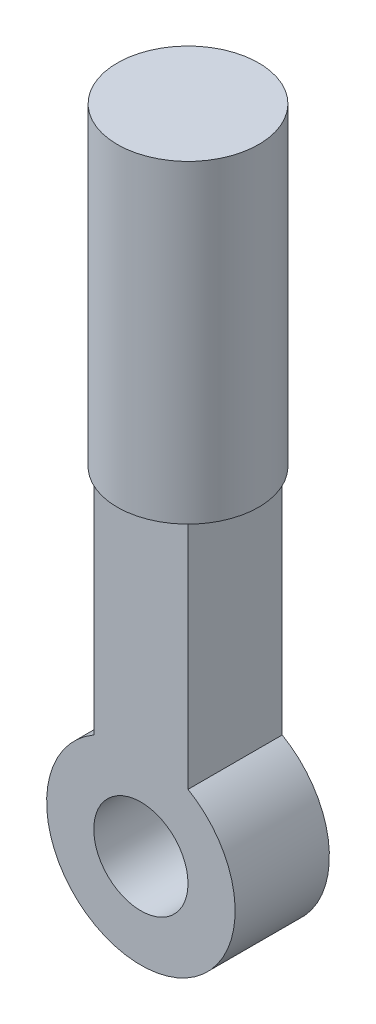
SolidWorks part; units mm, degrees
ref_plane "Front" through (0, 0, 0) normal (0, 0, 1) x (1, 0, 0)
ref_plane "Top" through (0, 0, 0) normal (0, 1, 0) x (1, 0, 0)
ref_plane "Right" through (0, 0, 0) normal (1, 0, 0) x (0, 0, -1)
sketch "Croquis1" plane through (0, 0, 0) normal (0, 0, 1) x (1, 0, 0)
  line L0 (0, 0) -> (0, 10) construction
  line L1 (1.5, 10) -> (-1.5, 10)
  line L2 (-1.5, 10) -> (-1.5, 2.5981)
  line L3 (1.5, 10) -> (1.5, 2.5981)
  circle A0 centre (0, 0) radius 1.5
  arc A1 (-1.5, 2.5981) -> (1.5, 2.5981) centre (0, 0) ccw
  dimension "D1" = 3
  dimension "D2" = 6
  dimension "D3" = 10
  dimension "D4" = 1.5
extrude "Saliente-Extruir1" add sketch "Croquis1" along normal blind 3
sketch "Croquis2" plane through (0, 10, 0) normal (0, 1, 0) x (1, 0, 0)
  line L0 (1.5, 0) -> (-1.5, -3) construction
  line L1 (-1.5, -3) -> (-1.5, 0) construction
  line L2 (-1.5, 0) -> (1.5, -3) construction
  circle A0 centre (0, -1.5) radius 2.25
  dimension "D1" = 4.5
extrude "Saliente-Extruir2" add sketch "Croquis2" along normal blind 10
